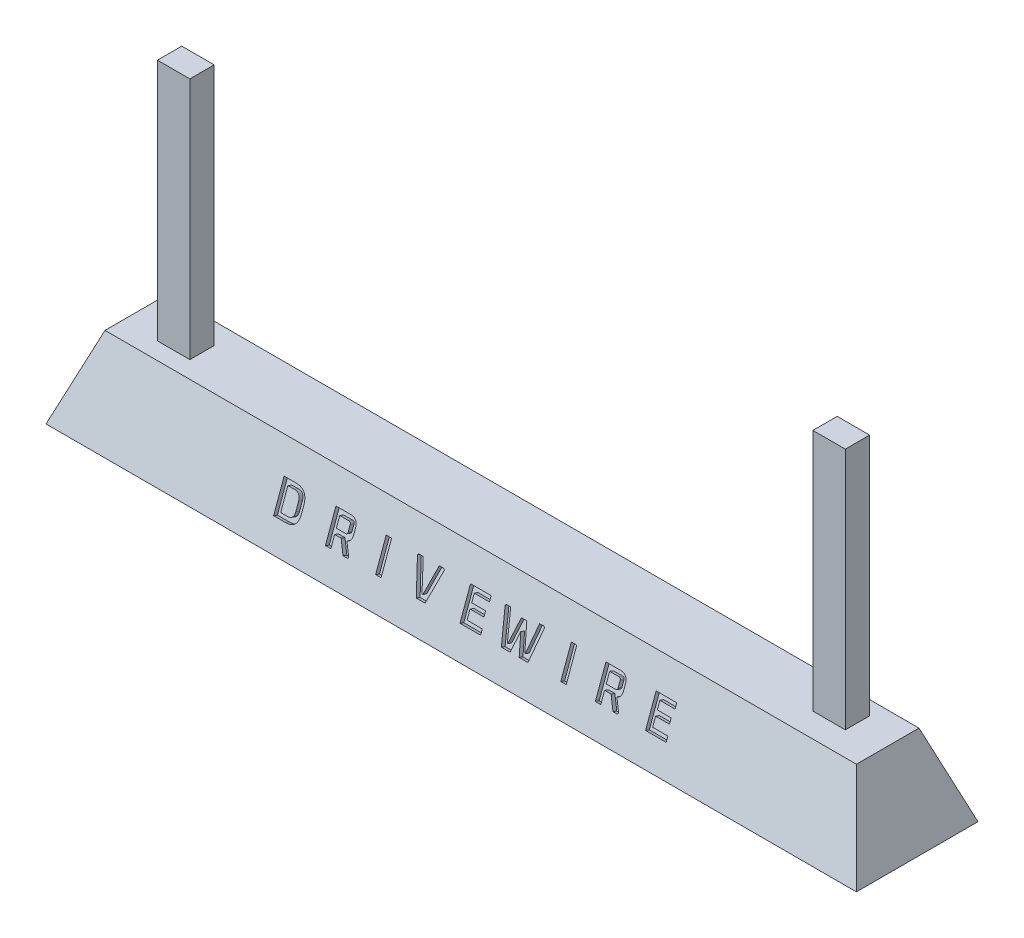
SolidWorks part; units mm, degrees
ref_plane "Front Plane" through (0, 0, 0) normal (0, 0, 1) x (1, 0, 0)
ref_plane "Top Plane" through (0, 0, 0) normal (0, 1, 0) x (1, 0, 0)
ref_plane "Right Plane" through (0, 0, 0) normal (1, 0, 0) x (0, 0, -1)
sketch "Sketch1" plane through (0, 0, 0) normal (0, 1, 0) x (1, 0, 0)
  line L1 (-100, -15) -> (100, -15)
  line L2 (-100, -15) -> (-100, 15)
  line L3 (-100, 15) -> (100, 15)
  line L4 (100, -15) -> (100, 15)
  line L5 (-100, -15) -> (100, 15) construction
  line L6 (-100, 15) -> (100, -15) construction
  point P0 (0, 0)
  point P6 (0, 0)
  point P13 (-90.6993, -8.237)
  point P14 (89.6475, -8.9306)
  dimension "D1" = 30
  dimension "D2" = 200
extrude "Boss-Extrude1" add sketch "Sketch1" along normal blind 20 draft 20
sketch "Sketch2" plane through (0, 0, 0) normal (0, 1, 0) x (1, 0, 0)
  point P0 (0, 0)
  point P6 (0, 0)
sketch "Sketch3" plane through (0, 20, 0) normal (0, 1, 0) x (1, 0, 0)
  line L2 (-84, -3.4949) -> (-76, -3.4949)
  line L3 (-84, -3.4949) -> (-84, 2.5051)
  line L4 (-84, 2.5051) -> (-76, 2.5051)
  line L5 (-76, -3.4949) -> (-76, 2.5051)
  line L6 (-84, -3.4949) -> (-76, 2.5051) construction
  line L7 (-84, 2.5051) -> (-76, -3.4949) construction
  line L9 (84, 4.2551) -> (76, -1.7449) construction
  line L10 (84, -1.7449) -> (76, 4.2551) construction
  line L11 (76, -1.7449) -> (76, 4.2551)
  line L12 (84, 4.2551) -> (76, 4.2551)
  line L13 (84, -1.7449) -> (84, 4.2551)
  line L14 (84, -1.7449) -> (76, -1.7449)
  point P1 (0, 0)
  point P2 (0, 0)
  point P3 (-80, -0.4949)
  point P9 (76, 3.2551)
  point P10 (76, 4.2551)
  point P15 (80, -0.4949)
  dimension "D1" = 8
  dimension "D2" = 6
  dimension "D3" = 80
  dimension "D4" = 6
extrude "Boss-Extrude3" add sketch "Sketch3" along normal blind 60
sketch "Sketch4" plane through (0, 4.8209, 13.2453) normal (0, 0.342, 0.9397) x (1, 0, 0)
  text T0 "D  R  I  V  E W  I  R  E" font "Oxanium SemiBold" height in points 28
extrude "Cut-Extrude2" cut sketch "Sketch4" against normal blind 1
